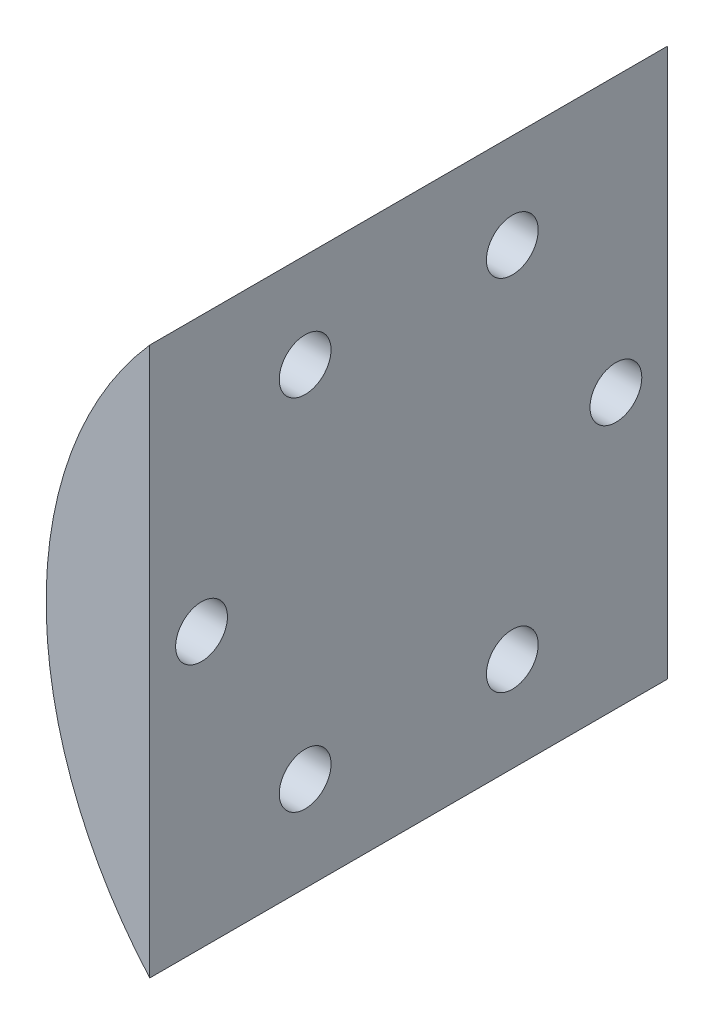
SolidWorks part; units mm, degrees
ref_plane "Front Plane" through (0, 0, 0) normal (0, 0, 1) x (1, 0, 0)
ref_plane "Top Plane" through (0, 0, 0) normal (0, 1, 0) x (1, 0, 0)
ref_plane "Right Plane" through (0, 0, 0) normal (1, 0, 0) x (0, 0, -1)
sketch "Sketch2" plane through (0, 0, 0) normal (0, 0, 1) x (1, 0, 0)
  line L0 (-30, 26.4575) -> (-30, -26.4575)
  circle A0 centre (0, 0) radius 40 construction
  arc A1 (-30, 26.4575) -> (-30, -26.4575) centre (0, 0) ccw
  dimension "D1" = 80
  dimension "D2" = 30
extrude "Boss-Extrude1" add sketch "Sketch2" along normal blind 50 contours L0 A1
sketch "Sketch3" plane through (-30, 0, 0) normal (1, 0, 0) x (0, 0, -1)
  line L0 (-50, 26.4575) -> (0, -26.4575) construction
  circle A0 centre (-25, 0) radius 20 construction
  circle A1 centre (-5, 0) radius 2.5
  circle A2 centre (-15, -17.3205) radius 2.5
  circle A3 centre (-35, -17.3205) radius 2.5
  circle A4 centre (-45, 0) radius 2.5
  circle A5 centre (-35, 17.3205) radius 2.5
  circle A6 centre (-15, 17.3205) radius 2.5
  point P9 (0, 0)
  point P10 (0, 0)
  point P20 (-25, 0)
  point P21 (0, 0)
  dimension "D1" = 40
  dimension "D2" = 5
  dimension "D3" = 6
extrude "Cut-Extrude1" cut sketch "Sketch3" against normal through all
